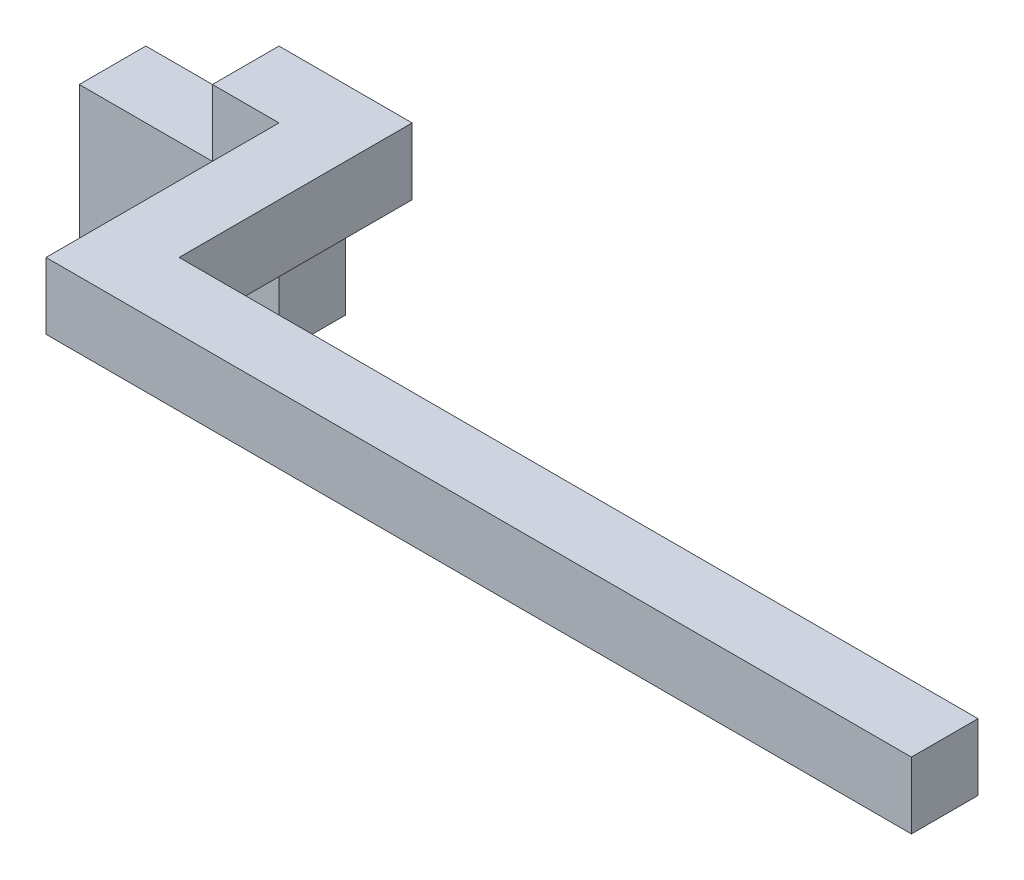
SolidWorks part; units mm, degrees
material "1060 Alloy"
ref_plane "Front Plane" through (0, 0, 0) normal (0, 0, 1) x (1, 0, 0)
ref_plane "Top Plane" through (0, 0, 0) normal (0, 1, 0) x (1, 0, 0)
ref_plane "Right Plane" through (0, 0, 0) normal (1, 0, 0) x (0, 0, -1)
ref_plane "Plane1" through (0, 0, 25.4) normal (0, 0, 1) x (1, 0, 0)
sketch "Sketch1" plane through (0, 0, 25.4) normal (0, 0, 1) x (1, 0, 0)
  line L0 (330.2, 25.4) -> (-76.2, 25.4)
  line L1 (-76.2, 25.4) -> (-76.2, -50.8)
  line L2 (-76.2, -50.8) -> (330.2, -50.8)
  line L3 (330.2, -50.8) -> (330.2, 25.4)
extrude "Boss-Extrude1" add sketch "Sketch1" against normal blind 25.4
sketch "Sketch2" plane through (0, 0, 0) normal (0, 0, -1) x (-1, 0, 0)
  line L0 (0, -50.8) -> (0, 0)
  line L1 (0, 0) -> (-330.2, 0)
  line L2 (-330.2, 0) -> (-330.2, -50.8)
  line L3 (-330.2, -50.8) -> (0, -50.8)
extrude "Cut-Extrude1" cut sketch "Sketch2" against normal through all
sketch "Sketch3" plane through (0, 0, 25.4) normal (0, 0, 1) x (1, 0, 0)
  line L0 (330.2, 0) -> (0, 0)
  line L1 (0, 0) -> (0, 25.4)
  line L2 (0, 25.4) -> (330.2, 25.4)
  line L3 (330.2, 25.4) -> (330.2, 0)
extrude "Boss-Extrude2" add sketch "Sketch3" along normal blind 88.9
sketch "Sketch4" plane through (0, 0, 25.4) normal (0, 0, 1) x (1, 0, 0)
  line L0 (-76.2, 0) -> (-25.4, 0)
  line L1 (-25.4, 0) -> (-25.4, 25.4)
  line L2 (-25.4, 25.4) -> (-76.2, 25.4)
  line L3 (-76.2, 25.4) -> (-76.2, 0)
extrude "Cut-Extrude2" cut sketch "Sketch4" against normal through all
sketch "Sketch5" plane through (0, 25.4, 0) normal (0, 1, 0) x (-1, 0, 0)
  line L0 (-25.4, 0) -> (-25.4, 88.9)
  line L1 (-25.4, 88.9) -> (-330.2, 88.9)
  line L2 (-330.2, 88.9) -> (-330.2, 0)
  line L3 (-330.2, 0) -> (-25.4, 0)
extrude "Cut-Extrude3" cut sketch "Sketch5" against normal through all
hole_wizard "Hole1" positions "Sketch7" profile "Sketch6" legacy
sketch "Sketch7" plane through (0, 0, 0) normal (0, 0, -1) x (-1, 0, 0)
  point P0 (-12.7, 12.7)
sketch "Sketch6" plane through (12.7, 12.7, 0) normal (1, 0, 0) x (0, 1, 0)
  line L0 (0, 0) -> (0, 3.302)
  line L1 (0, 3.302) -> (6.35, 3.302)
  line L2 (6.35, 3.302) -> (6.35, 0)
  line L3 (6.35, 0) -> (0, 0)
  line L4 (0, 110) -> (0, -10) construction
  dimension "Diameter" = 12.7
  dimension "Depth" = 3.302
